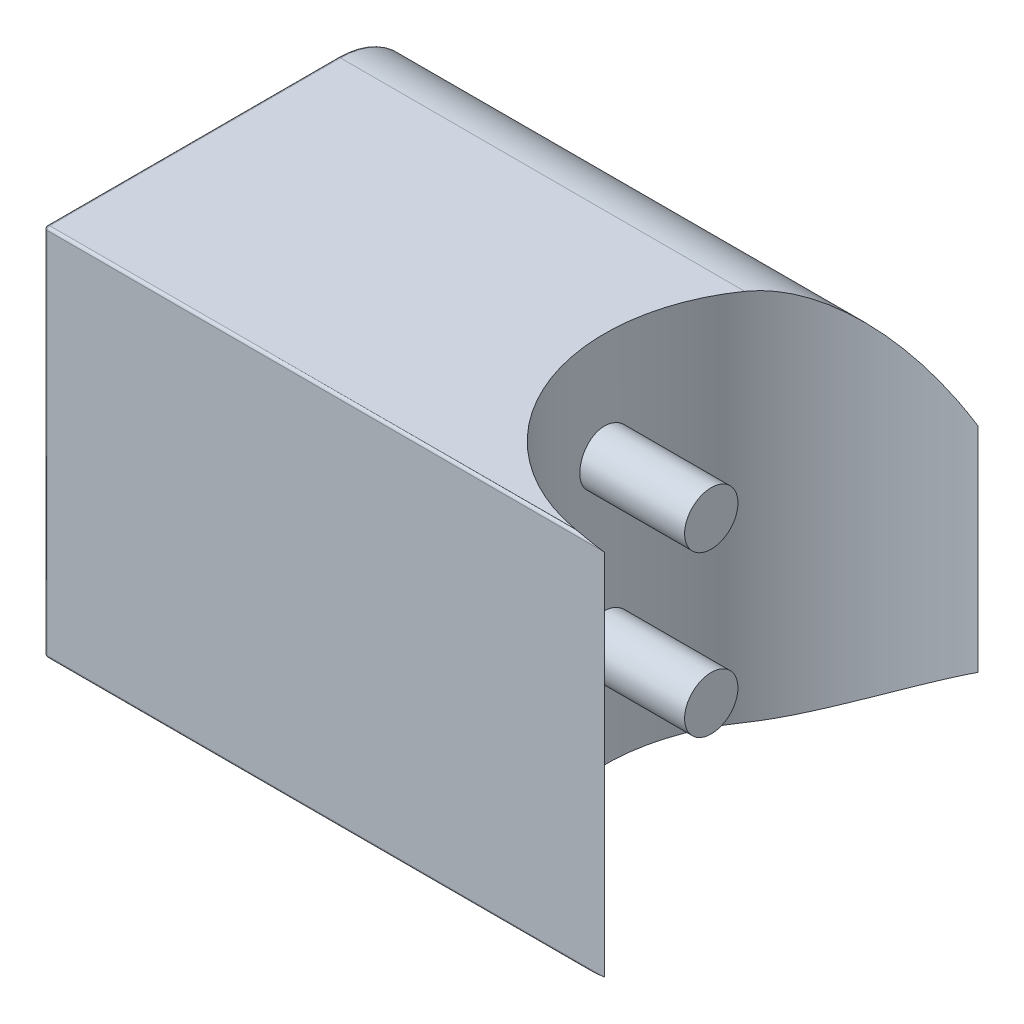
SolidWorks part; units mm, degrees
ref_plane "Front Plane" through (0, 0, 0) normal (0, 0, 1) x (1, 0, 0)
ref_plane "Top Plane" through (0, 0, 0) normal (0, 1, 0) x (1, 0, 0)
ref_plane "Right Plane" through (0, 0, 0) normal (1, 0, 0) x (0, 0, -1)
sketch "Sketch1" plane through (0, 0, 0) normal (1, 0, 0) x (0, 0, -1)
  line L1 (0, 0) -> (140, 0)
  line L2 (0, 0) -> (0, -140)
  line L3 (0, -140) -> (140, -140)
  line L4 (140, 0) -> (140, -140)
  point P7 (0, 0)
  dimension "D1" = 140
  dimension "D2" = 140
extrude "Boss-Extrude1" add sketch "Sketch1" along normal blind 140
sketch "Sketch2" plane through (0, 0, 0) normal (-1, 0, 0) x (0, 0, 1)
  line L0 (-140, 0) -> (0, 0) construction
  line L1 (-140, -140) -> (-140, 0) construction
  circle A0 centre (-70, -70) radius 60
  dimension "D3" = 120
  dimension "D1" = 70
  dimension "D2" = 70
extrude "Cut-Extrude1" cut sketch "Sketch2" against normal blind 130 draft 24
sketch "Sketch3" plane through (0, 0, 0) normal (0, 0, 1) x (1, 0, 0)
  line L0 (140, 0) -> (0, 0) construction
  line L1 (0, 0) -> (0, -140) construction
  circle A0 centre (20, -70) radius 10
  dimension "D2" = 70
  dimension "D1" = 20
  dimension "D3" = 20
extrude "Boss-Extrude2" add sketch "Sketch3" against normal blind 140
sketch "Sketch4" plane through (0, -140, 0) normal (0, -1, 0) x (-1, 0, 0)
  line L0 (-140, 0) -> (-140, 140) construction
  line L1 (-140, 140) -> (0, 140) construction
  line L2 (-140, 0) -> (-210, 0)
  line L3 (-140, 140) -> (-210, 140)
  line L4 (-140, 0) -> (-140, 140)
  arc A0 (-210, 0) -> (-210, 140) centre (-210, 70) ccw
  line M3 (-140, 140) -> (-140, 0)
  dimension "D1" = 70
  dimension "D2" = 70
  dimension "D3" = 140
extrude "Boss-Extrude3" add sketch "Sketch4" against normal blind 140 contours A0 L3 M3 | A0 L2 L4
ref_plane "Plane1" through (140, 0, 0) normal (1, 0, 0) x (0, 0, -1)
sketch "Sketch5" plane through (140, 0, 0) normal (1, 0, 0) x (0, 0, -1)
  line L0 (0, -140) -> (140, -140) construction
  line L1 (140, 0) -> (0, 0) construction
  line L2 (140, 0) -> (140, -140) construction
  circle A0 centre (70, -100) radius 10
  circle A1 centre (70, -40) radius 10
  dimension "D3" = 20
  dimension "D4" = 20
  dimension "D1" = 40
  dimension "D2" = 40
  dimension "D5" = 70
  dimension "D6" = 70
extrude "Boss-Extrude4" add sketch "Sketch5" along normal blind 40
fillet "Fillet1" radius 30 2 edges at (105, 0, -140) (105, -140, -140)
fillet "Fillet2" radius 1 8 edges at (0, -140, -55) (0, -131.2132, -131.2132) (0, -70, -140) (0, -8.7868, -131.2132) (0, 0, -55) (105, 0, 0) (105, -140, 0) (0, -70, 0)
equation "\"D1@Sketch2\"=\"D2@Sketch1\"/2"
equation "\"D2@Sketch2\"=\"D1@Sketch1\"/2"
equation "\"D2@Sketch3\"=\"D2@Sketch1\"/2"
equation "\"D2@Sketch4\"=\"D1@Sketch1\"/2"
equation "\"D5@Sketch5\"=\"D1@Sketch1\"/2"
equation "\"D6@Sketch5\"=\"D5@Sketch5\""
